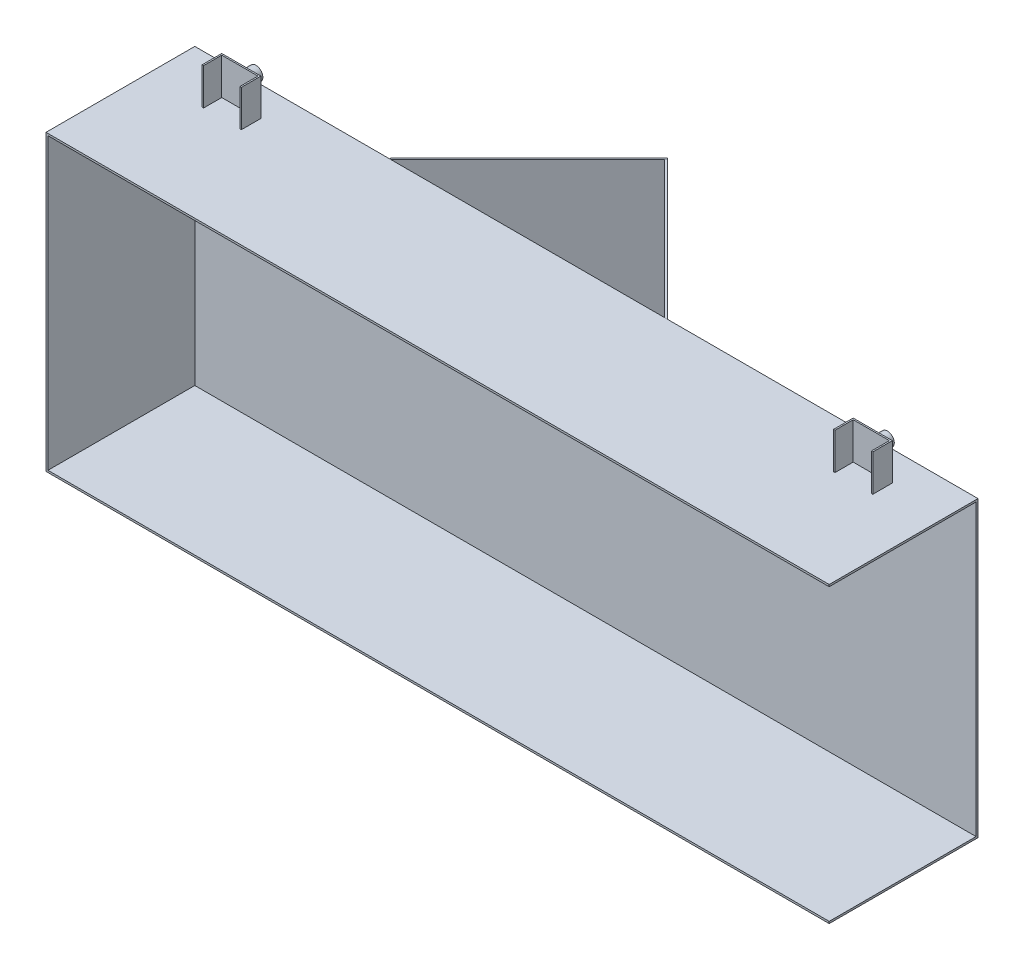
SolidWorks part; units mm, degrees
ref_plane "前视基准面" through (0, 0, 0) normal (0, 0, 1) x (1, 0, 0)
ref_plane "上视基准面" through (0, 0, 0) normal (0, 1, 0) x (1, 0, 0)
ref_plane "右视基准面" through (0, 0, 0) normal (1, 0, 0) x (0, 0, -1)
sketch "草图1" plane through (0, 0, 0) normal (0, 0, 1) x (1, 0, 0)
  line L1 (-800, -300) -> (800, -300)
  line L2 (-800, -300) -> (-800, 300)
  line L3 (-800, 300) -> (800, 300)
  line L4 (800, -300) -> (800, 300)
  line L5 (-800, -300) -> (800, 300) construction
  line L6 (-800, 300) -> (800, -300) construction
  point P0 (0, 0)
  dimension "D1" = 1600
  dimension "D2" = 600
extrude "凸台-拉伸1" add sketch "草图1" along normal blind 4 contours L3 L4 L1 L2
sketch "草图2" plane through (0, 0, 4) normal (0, 0, 1) x (1, 0, 0)
  line L0 (796, 296) -> (-796, 296)
  line L1 (-796, 296) -> (-796, -296)
  line L2 (-796, -296) -> (796, -296)
  line L3 (796, 296) -> (800, 296)
  line L4 (-800, 300) -> (-800, -300)
  line L5 (-800, -300) -> (800, -300)
  line L6 (800, -300) -> (800, 300)
  line L7 (800, 300) -> (-800, 300)
  line L8 (-800, 300) -> (-800, -300)
  line L9 (-800, -300) -> (800, -300)
  line L10 (800, -300) -> (800, 300) construction
  line L11 (800, 300) -> (-800, 300)
  line L12 (800, 296) -> (800, 300)
  line L13 (796, -296) -> (800, -296)
  line L14 (800, -296) -> (800, -300)
  line L16 (796, -296) -> (796, 296) construction
  line L17 (800, -300) -> (800, 300) construction
  dimension "D1" = 0
  dimension "D2" = 4
extrude "凸台-拉伸2" add sketch "草图2" along normal blind 300
sketch "草图3" plane through (0, -300, 0) normal (0, -1, 0) x (1, 0, 0)
  line L0 (685, 100) -> (685, 60)
  line L1 (682, 100) -> (682, 63)
  line L2 (685, 60) -> (605, 60)
  line L3 (605, 60) -> (605, 100)
  line L4 (-685, 100) -> (-685, 60)
  line L5 (-685, 60) -> (-605, 60)
  line L6 (-605, 60) -> (-605, 100)
  line L7 (-605, 60) -> (605, 60) construction
  line L8 (-800, 0) -> (800, 0) construction
  line L9 (682, 63) -> (608, 63)
  line L10 (608, 63) -> (608, 100)
  line L11 (-682, 100) -> (-682, 63)
  line L12 (-682, 63) -> (-608, 63)
  line L13 (-608, 63) -> (-608, 100)
  line L14 (608, 100) -> (605, 100)
  line L15 (682, 100) -> (685, 100)
  line L16 (-685, 100) -> (-682, 100)
  line L17 (-608, 100) -> (-605, 100)
  point P8 (0, 60)
  dimension "D1" = 80
  dimension "D2" = 40
  dimension "D3" = 80
  dimension "D4" = 40
  dimension "D5" = 1210
  dimension "D6" = 60
  dimension "D7" = 3
  dimension "D8" = 3
extrude "凸台-拉伸3" add sketch "草图3" along normal blind 75
sketch "草图4" plane through (0, 0, 60) normal (0, 0, -1) x (-1, 0, 0)
  line L1 (-605, -375) -> (-685, -375) construction
  line L4 (685, -375) -> (605, -375) construction
  circle A0 centre (-645, -343) radius 14
  circle A1 centre (645, -345) radius 14
  point P4 (0, 0)
  point P7 (-645, -375)
  point P9 (645, -375)
  dimension "D1" = 28
  dimension "D3" = 28
  dimension "D2" = 32
  dimension "D4" = 30
sketch "草图5" plane through (0, 0, 0) normal (0, 0, -1) x (-1, 0, 0)
  line L0 (400, -300) -> (400, 300)
  line L1 (800, -300) -> (-800, -300) construction
  line L2 (800, 300) -> (-800, 300) construction
  line L3 (800, -300) -> (800, 300) construction
  dimension "D1" = 400
ref_plane "基准面1" through (-200, 0, 200) normal (-0.7071, 0, 0.7071) x (0, 1, 0)
sketch "草图6" plane through (-200, 0, 200) normal (-0.7071, 0, 0.7071) x (0, 1, 0)
  line L0 (-300, 282.8427) -> (300, 282.8427) construction
  line L1 (300, 282.8427) -> (-300, 282.8427)
  line L2 (300, 282.8427) -> (300, 286.8427)
  line L3 (300, 286.8427) -> (-300, 286.8427)
  line L4 (-300, 282.8427) -> (-300, 286.8427)
  line L5 (300, 282.8427) -> (-300, 286.8427) construction
  line L6 (300, 286.8427) -> (-300, 282.8427) construction
  point P0 (0, 284.8427)
  point P7 (0, 0)
  dimension "D1" = 0
  dimension "D2" = 600
  dimension "D3" = 4
extrude "凸台-拉伸5" add sketch "草图6" against normal blind 400 separate body
sketch "草图7" plane through (-200, 0, -200) normal (0.7071, 0, 0.7071) x (0.7071, 0, -0.7071)
  line L0 (117.1573, -300) -> (117.1573, 300) construction
  line L1 (117.1573, -300) -> (117.1573, 300)
  line L2 (113.1573, -300) -> (113.1573, 300)
  line L3 (117.1573, -300) -> (113.1573, -300)
  line L4 (113.1573, 300) -> (117.1573, 300)
  dimension "D1" = 4
extrude "凸台-拉伸9" add sketch "草图7" along normal up to surface (400 mm away) separate body
extrude "凸台-拉伸10" add sketch "草图4" along normal blind 30
mirror "镜向3" about plane through (0, 0, 0) normal (0, 1, 0) of "凸台-拉伸3", "凸台-拉伸10"
sketch "草图8" plane through (-202.8284, 0, -202.8284) normal (-0.7071, 0, -0.7071) x (-0.7071, 0, 0.7071)
  line L0 (127.8427, 75) -> (127.8427, -75) construction
  line L1 (127.8427, -75) -> (37.8427, -75) construction
  line L2 (37.8427, -75) -> (37.8427, 75) construction
  line L3 (127.8427, 75) -> (37.8427, 75) construction
  line L4 (-117.1573, -300) -> (282.8427, -300) construction
  circle A0 centre (127.8427, 75) radius 7
  circle A1 centre (127.8427, -75) radius 7
  circle A2 centre (37.8427, -75) radius 7
  circle A3 centre (37.8427, 75) radius 7
  point P8 (37.8427, 0)
  point P9 (82.8427, -75)
  point P13 (82.8427, -300)
  dimension "D3" = 14
  dimension "D1" = 150
  dimension "D2" = 90
extrude "切除-拉伸1" cut sketch "草图8" against normal blind 20
